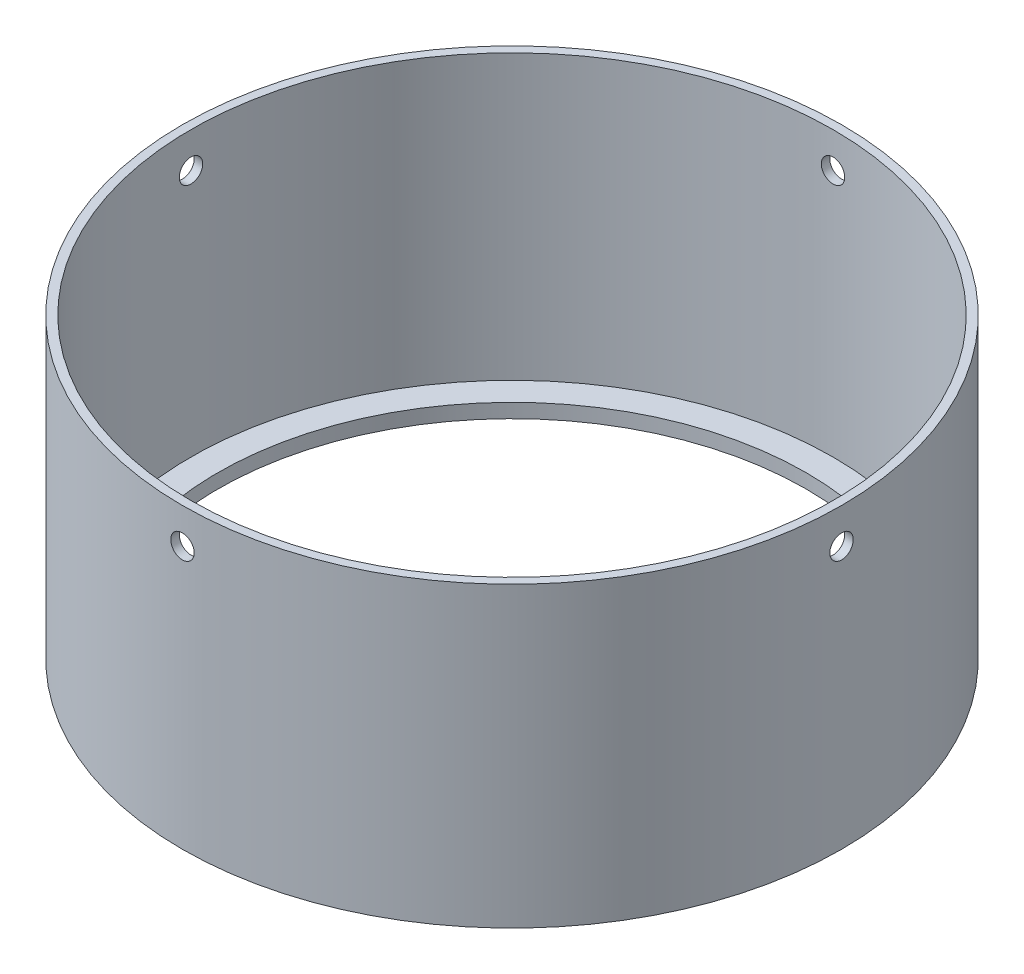
SolidWorks part; units mm, degrees
ref_plane "Front Plane" through (0, 0, 0) normal (0, 0, 1) x (1, 0, 0)
ref_plane "Top Plane" through (0, 0, 0) normal (0, 1, 0) x (1, 0, 0)
ref_plane "Right Plane" through (0, 0, 0) normal (1, 0, 0) x (0, 0, -1)
sketch "Sketch1" plane through (0, 0, 0) normal (0, 1, 0) x (1, 0, 0)
  circle A0 centre (0, 0) radius 45.3
  circle A1 centre (0, 0) radius 46.5
  dimension "D1" = 90.6
  dimension "D2" = 1.2
extrude "Boss-Extrude1" add sketch "Sketch1" along normal blind 40
sketch "Sketch2" plane through (0, 0, 0) normal (1, 0, 0) x (0, 0, -1)
  line L0 (0, 0) -> (0, 35) construction
  circle A0 centre (0, 35) radius 1.65
  dimension "D1" = 3.3
  dimension "D2" = 35
extrude "Cut-Extrude1" cut sketch "Sketch2" against normal through all
pattern_circular "CirPattern1" count 4 over 360 about axis through (0, 40, 0) along (0, -1, 0) of "Cut-Extrude1"
sketch "Sketch3" plane through (0, 0, 0) normal (0, -1, 0) x (1, 0, 0)
  circle A0 centre (0, 0) radius 46.5 construction
  circle A1 centre (0, 0) radius 46.5
  circle A2 centre (0, 0) radius 41.5
  dimension "D1" = 5
extrude "Boss-Extrude2" add sketch "Sketch3" along normal blind 2
